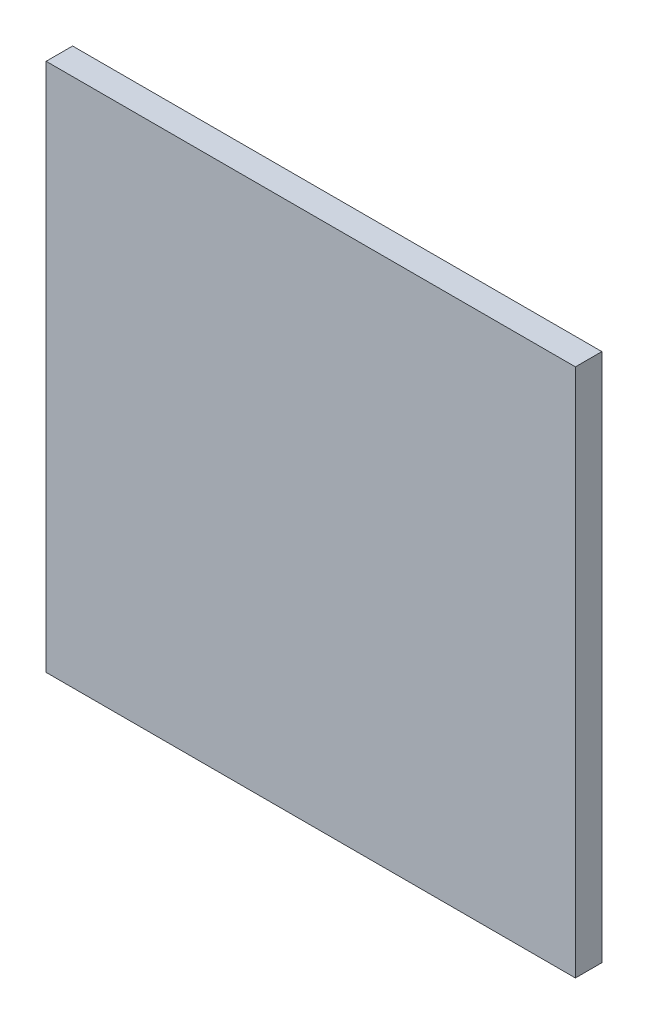
SolidWorks part; units mm, degrees
ref_plane "Plano frontal" through (0, 0, 0) normal (0, 0, 1) x (1, 0, 0)
ref_plane "Plano superior" through (0, 0, 0) normal (0, 1, 0) x (1, 0, 0)
ref_plane "Plano direito" through (0, 0, 0) normal (1, 0, 0) x (0, 0, -1)
sketch "Esboço1" plane through (0, 0, 0) normal (0, 0, 1) x (1, 0, 0)
  line L1 (0, 0) -> (-60, 0)
  line L2 (0, 0) -> (0, 60)
  line L3 (0, 60) -> (-60, 60)
  line L4 (-60, 0) -> (-60, 60)
  dimension "D1" = 60
  dimension "D2" = 60
extrude "Ressalto-extrusão1" add sketch "Esboço1" along normal blind 3
